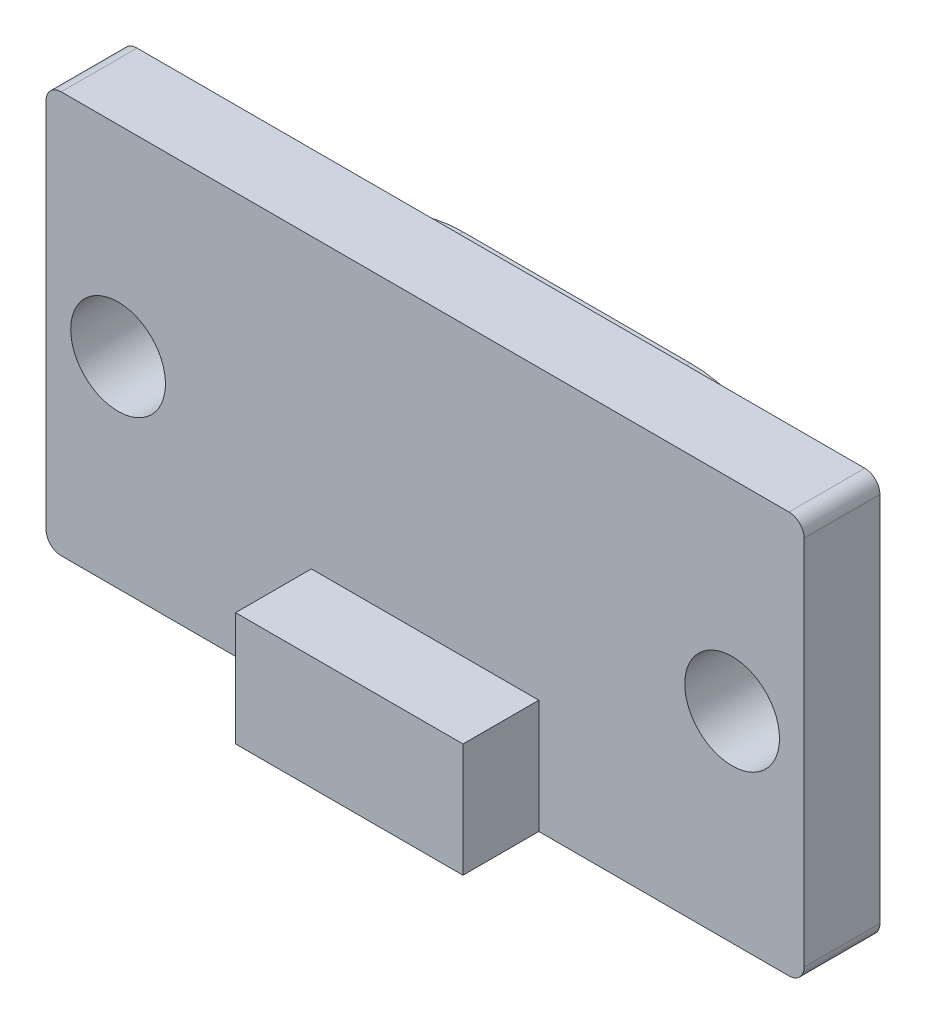
SolidWorks part; units mm, degrees
ref_plane "前视基准面" through (0, 0, 0) normal (0, 0, 1) x (1, 0, 0)
ref_plane "上视基准面" through (0, 0, 0) normal (0, 1, 0) x (1, 0, 0)
ref_plane "右视基准面" through (0, 0, 0) normal (1, 0, 0) x (0, 0, -1)
sketch "草图1" plane through (0, 0, 0) normal (0, 0, 1) x (1, 0, 0)
  line L0 (0, 0) -> (0, 6.3713) construction
  line L1 (-10, -5.3) -> (10, -5.3)
  line L2 (-10, -5.3) -> (-10, 5.3)
  line L3 (-10, 5.3) -> (10, 5.3)
  line L4 (10, -5.3) -> (10, 5.3)
  line L5 (-10, -5.3) -> (10, 5.3) construction
  line L6 (-10, 5.3) -> (10, -5.3) construction
  circle A0 centre (8.1, 0) radius 1.25
  circle A1 centre (-8.1, 0) radius 1.25
  point P0 (0, 0)
  dimension "D1" = 2.5
  dimension "D2" = 16.2
  dimension "D3" = 20
  dimension "D4" = 10.6
extrude "凸台-拉伸1" add sketch "草图1" along normal blind 2
sketch "草图2" plane through (0, 0, 0) normal (0, 0, -1) x (-1, 0, 0)
  line L0 (-3, 0) -> (3, 0) construction
  line L1 (-3, 3.4) -> (3, 3.4)
  line L2 (-3, -3.4) -> (3, -3.4)
  arc A0 (-3, 3.4) -> (-3, -3.4) centre (-3, 0) ccw
  arc A1 (3, -3.4) -> (3, 3.4) centre (3, 0) ccw
  point P2 (0, 0)
  dimension "D2" = 3.4
  dimension "D1" = 6
extrude "凸台-拉伸2" add sketch "草图2" along normal blind 2
sketch "草图3" plane through (0, 0, 2) normal (0, 0, 1) x (1, 0, 0)
  line L0 (-10, -5.3) -> (10, -5.3) construction
  line L1 (-3, -2.3) -> (3, -2.3)
  line L2 (-3, -2.3) -> (-3, -5.3)
  line L3 (-3, -5.3) -> (3, -5.3)
  line L4 (3, -2.3) -> (3, -5.3)
  line L5 (-3, -2.3) -> (3, -5.3) construction
  line L6 (-3, -5.3) -> (3, -2.3) construction
  point P0 (0, -3.8)
  dimension "D1" = 6
  dimension "D2" = 3
extrude "凸台-拉伸3" add sketch "草图3" along normal blind 2
fillet "圆角1" radius 0.4 4 edges at (10, -5.3, 1) (-10, -5.3, 1) (-10, 5.3, 1) (10, 5.3, 1)
